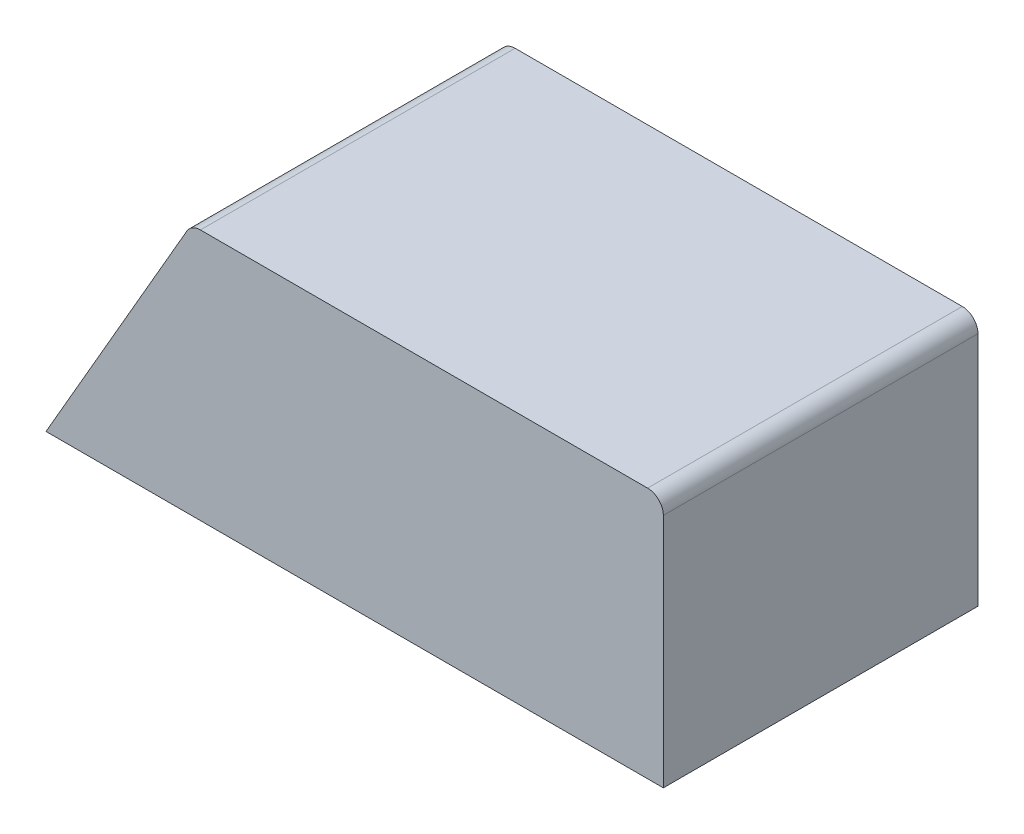
SolidWorks part; units mm, degrees
material "Acier non allié"
ref_plane "Plan de face" through (0, 0, 0) normal (0, 0, 1) x (1, 0, 0)
ref_plane "Plan de dessus" through (0, 0, 0) normal (0, 1, 0) x (1, 0, 0)
ref_plane "Plan de droite" through (0, 0, 0) normal (1, 0, 0) x (0, 0, -1)
sketch "Esquisse1" plane through (0, 0, 0) normal (0, 0, 1) x (1, 0, 0)
  line L0 (-15, 8) -> (0, 8)
  line L1 (0, 8) -> (0, 0)
  line L2 (0, 0) -> (-19.6188, 0)
  line L3 (-19.6188, 0) -> (-15, 8)
  dimension "D1" = 15
  dimension "D2" = 8
  dimension "D3" = 120
extrude "Boss.-Extru.1" add sketch "Esquisse1" along normal mid plane 10
fillet "Congé1" radius 0.5 2 edges at (0, 8, 0) (-15, 8, 0)
